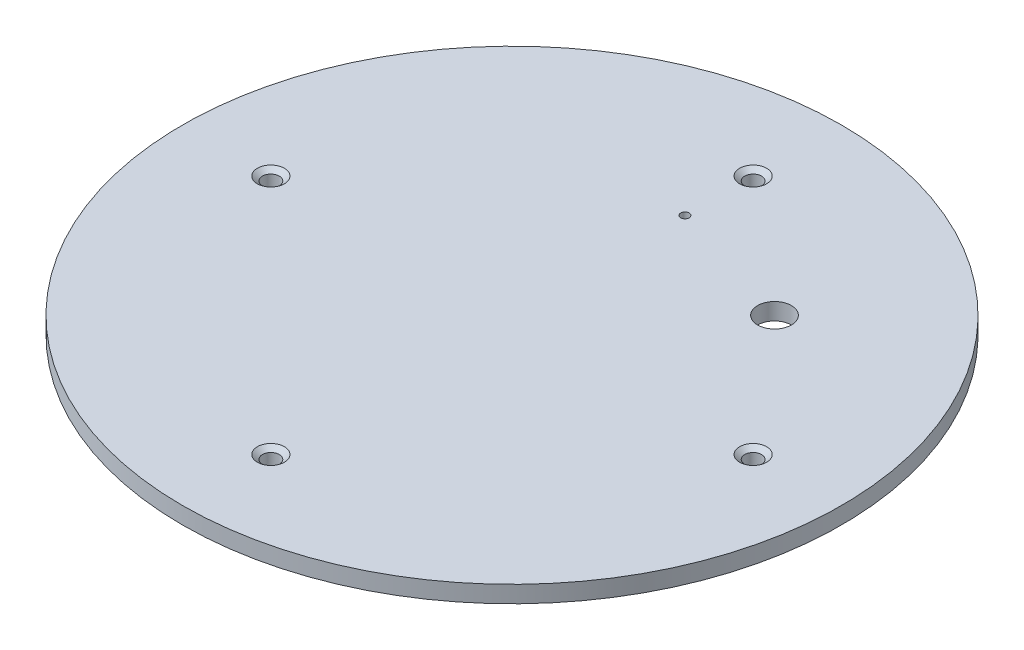
SolidWorks part; units mm, degrees
material "1060 Alloy"
ref_plane "Front Plane" through (0, 0, 0) normal (0, 0, 1) x (1, 0, 0)
ref_plane "Top Plane" through (0, 0, 0) normal (0, 1, 0) x (1, 0, 0)
ref_plane "Right Plane" through (0, 0, 0) normal (1, 0, 0) x (0, 0, -1)
sketch "Sketch1" plane through (0, 0, 0) normal (0, 1, 0) x (1, 0, 0)
  circle A0 centre (0, 0) radius 19.53
  dimension "D1" = 39.06
extrude "Boss-Extrude1" add sketch "Sketch1" along normal blind 1
hole_wizard "CSK for M2 Flat Head Machine Screw1" positions "Sketch2" profile "Sketch3" countersink size "M2" standard "ANSI Metric" end condition through all
sketch "Sketch2" plane through (0, 1, 0) normal (0, 1, 0) x (1, 0, 0)
  point P0 (0, 14.29)
  point P2 (14.29, 0)
  point P4 (0, -14.29)
  point P6 (-14.29, 0)
  dimension "D1" = 14.29
  dimension "D2" = 14.29
  dimension "D3" = 14.29
  dimension "D4" = 14.29
sketch "Sketch3" plane through (0, 1, -14.29) normal (1, 0, 0) x (0, 0, 1)
  line L0 (0, 0) -> (0, 1)
  line L1 (0, 1) -> (0.5, 1)
  line L2 (0.5, 1) -> (0.5, 0.2517)
  line L3 (0.5, 0.2517) -> (0.8, 0)
  line L5 (0.8, 0) -> (0, 0)
  line L6 (-0.5, 0.2517) -> (-0.8, 0) construction
  line L11 (0, -6.35) -> (0, 107.95) construction
  dimension "Thru Hole Dia." = 1
  dimension "Thru Hole Depth" = 1
  dimension "Near C'Sink Dia." = 1.6
  dimension "Near C'Sink Angle" = 100
sketch "Sketch5" plane through (0, 1, 0) normal (0, 1, 0) x (1, 0, 0)
  line L0 (0, 0) -> (12.6106, 12.6106) construction
  line L1 (0, 0) -> (20.4022, 0) construction
  circle A0 centre (0, 10.25) radius 0.25
  circle A1 centre (7.7782, 7.7782) radius 1
  dimension "D1" = 0.5
  dimension "D2" = 10.25
  dimension "D3" = 2
  dimension "D4" = 11
  dimension "D5" = 45
extrude "Cut-Extrude1" cut sketch "Sketch5" against normal through all both and the other way through all
